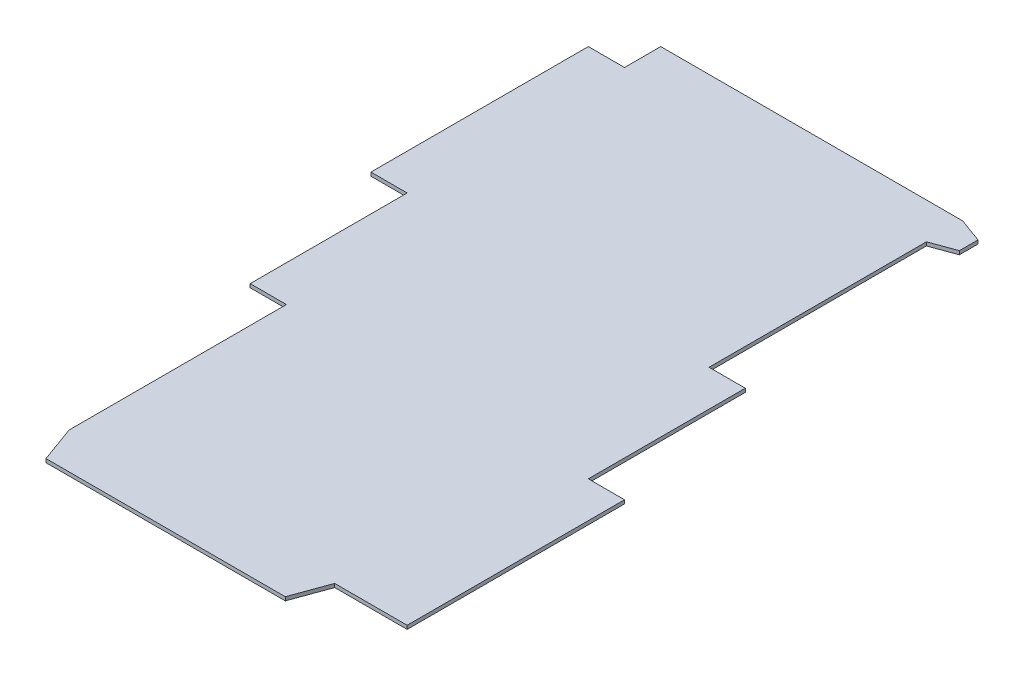
SolidWorks part; units mm, degrees
ref_plane "Alzado" through (0, 0, 0) normal (0, 0, 1) x (1, 0, 0)
ref_plane "Planta" through (0, 0, 0) normal (0, 1, 0) x (1, 0, 0)
ref_plane "Vista lateral" through (0, 0, 0) normal (1, 0, 0) x (0, 0, -1)
sketch "Croquis1" plane through (0, 0, 0) normal (0, 1, 0) x (1, 0, 0)
  line L0 (0, 0) -> (0, 90)
  line L1 (0, 90) -> (10, 93.6397)
  line L2 (10, 93.6397) -> (10, 101.3603)
  line L3 (10, 101.3603) -> (0, 105)
  line L4 (0, 105) -> (-110, 105)
  line L5 (-110, 105) -> (-125, 105)
  line L6 (-125, 105) -> (-125, 90)
  line L10 (-125, 0) -> (-140, 0)
  line L11 (-140, 0) -> (-140, 90)
  line L12 (-140, 90) -> (-125, 90)
  line L13 (-125, 0) -> (-125, -65)
  line L14 (-125, 90) -> (-125, 0) construction
  line L15 (-110, 90) -> (-110, 0) construction
  line L16 (-110, 90) -> (-110, 105) construction
  line L17 (-110, 0) -> (-110, -65) construction
  line L18 (-110, -65) -> (0, -65) construction
  line L19 (0, -65) -> (0, 0) construction
  line L20 (0, 0) -> (-110, 0) construction
  line L21 (-125, 0) -> (-110, 0) construction
  line L22 (-125, -65) -> (-110, -65)
  line L23 (-125, 90) -> (-110, 90) construction
  line L24 (-110, -65) -> (-110, -155)
  line L26 (-104.5404, -170) -> (-5.4596, -170)
  line L27 (-5.4596, -170) -> (0, -155)
  line L28 (0, -155) -> (-110, -155) construction
  line L29 (0, -65) -> (0, -155) construction
  line L30 (0, -65) -> (15, -65) construction
  line L31 (15, -65) -> (15, -155) construction
  line L32 (0, 90) -> (0, 105) construction
  line L33 (0, 0) -> (15, 0)
  line L34 (15, 0) -> (15, -65)
  line L35 (15, -65) -> (30, -65)
  line L36 (30, -65) -> (30, -155)
  line L37 (30, -155) -> (15, -155)
  line L38 (15, -155) -> (0, -155)
  line L39 (-110, 90) -> (0, 90) construction
  line L40 (0, 105) -> (66.4027, 105) construction
  line L41 (-110, -155) -> (-110, -208.4954) construction
  line L42 (0, -155) -> (0, -208.4954) construction
  line L43 (-110, -155) -> (-104.5404, -170)
  dimension "D1" = 90
  dimension "D2" = 110
  dimension "D3" = 110
  dimension "D4" = 20
  dimension "D5" = 10
  dimension "D6" = 15
  dimension "D7" = 90
  dimension "D8" = 65
  dimension "D9" = 15
  dimension "D10" = 15
  dimension "D11" = 15
  dimension "D12" = 15
  dimension "D13" = 20
  dimension "D14" = 20
  dimension "D15" = 15
extrude "Saliente-Extruir1" add sketch "Croquis1" along normal blind 1.5
